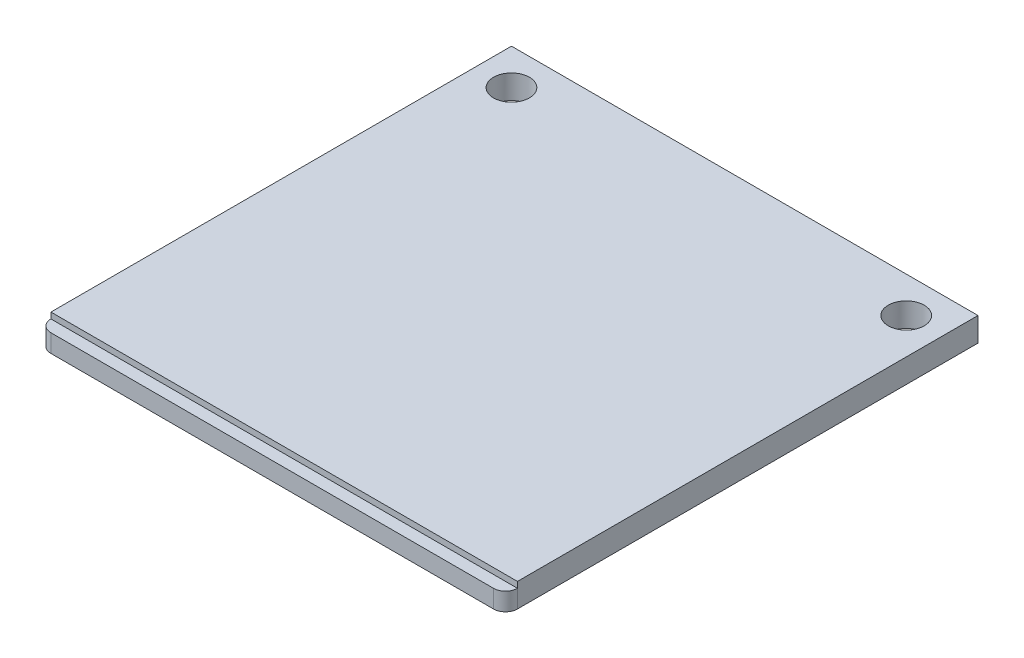
SolidWorks part; units mm, degrees
ref_plane "Ebene vorne" through (0, 0, 0) normal (0, 0, 1) x (1, 0, 0)
ref_plane "Ebene oben" through (0, 0, 0) normal (0, 1, 0) x (1, 0, 0)
ref_plane "Ebene rechts" through (0, 0, 0) normal (1, 0, 0) x (0, 0, -1)
sketch "Skizze1" plane through (0, 0, 0) normal (0, 1, 0) x (1, 0, 0)
  line L1 (0, 0) -> (39, 0)
  line L2 (0, 0) -> (0, 39.5)
  line L3 (0, 39.5) -> (39, 39.5)
  line L4 (39, 0) -> (39, 39.5)
  dimension "D1" = 39
  dimension "D2" = 39.5
extrude "Aufsatz-Linear austragen1" add sketch "Skizze1" along normal blind 2
sketch "Skizze2" plane through (0, 2, 0) normal (0, 1, 0) x (1, 0, 0)
  line L0 (0, 39.5) -> (0, 0) construction
  line L1 (39, 39.5) -> (0, 39.5) construction
  line L2 (39, 0) -> (39, 39.5) construction
  circle A0 centre (3, 36.5) radius 1.5
  circle A1 centre (36, 36.5) radius 1.5
  point P8 (0, 0)
  dimension "D1" = 3
  dimension "D2" = 3
  dimension "D3" = 3
  dimension "D4" = 3
extrude "Schnitt-Linear austragen1" cut sketch "Skizze2" against normal up to next
sketch "Skizze3" plane through (0, 2, 0) normal (0, 1, 0) x (1, 0, 0)
  line L0 (39, 0) -> (39, 39.5) construction
  line L2 (0, 0) -> (39, 0)
  line L3 (0, 0) -> (0, 1)
  line L4 (0, 1) -> (39, 1)
  line L5 (39, 0) -> (39, 1)
  dimension "D1" = 1
extrude "Schnitt-Linear austragen2" cut sketch "Skizze3" against normal blind 0.5
fillet "Verrundung1" radius 1 2 edges at (0, 0.75, 0) (39, 0.75, 0)
